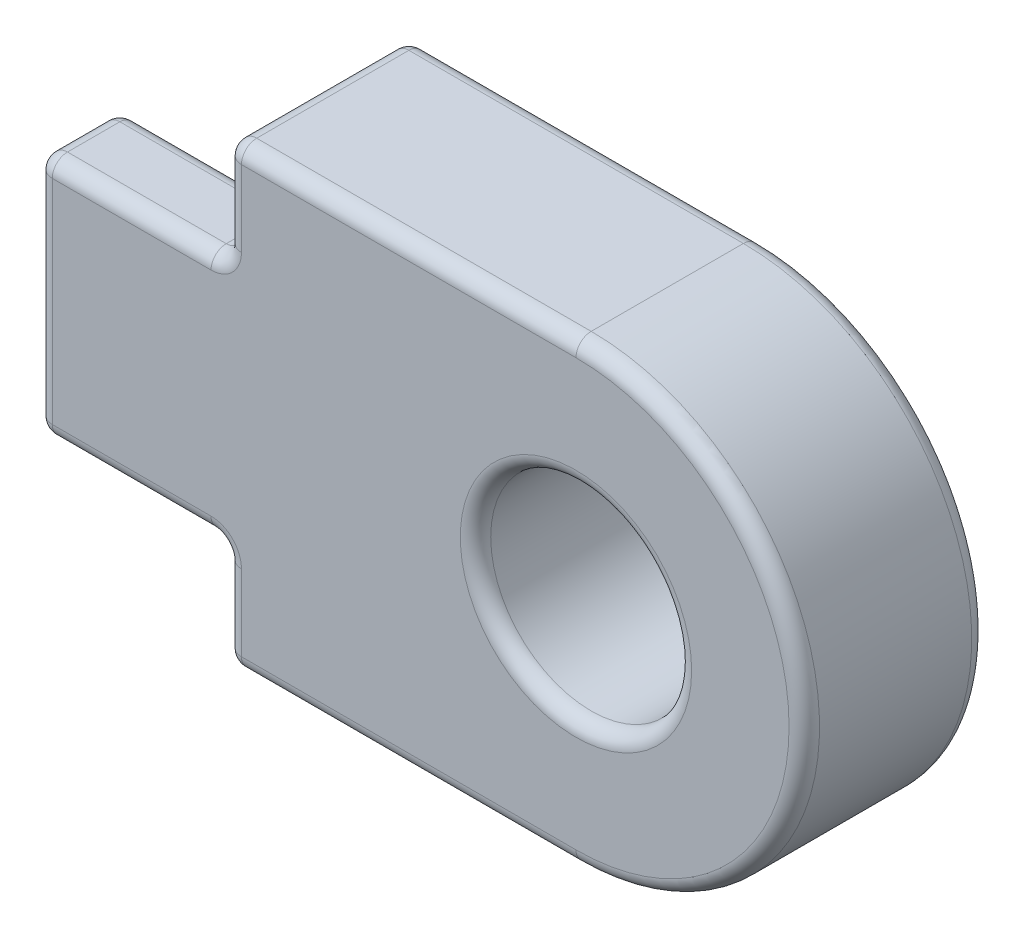
SolidWorks part; units mm, degrees
ref_plane "Front Plane" through (0, 0, 0) normal (1, 0, 0) x (0, 1, 0)
ref_plane "Top Plane" through (0, 0, 0) normal (0, 0, 1) x (0, 1, 0)
ref_plane "Right Plane" through (0, 0, 0) normal (0, 1, 0) x (-1, 0, 0)
sketch "Sketch1" plane through (0, 0, 0) normal (0, 0, 1) x (0, 1, 0)
  line L0 (-3.75, 0) -> (-3.75, 5.7439)
  line L1 (-3.75, 5.7439) -> (3.75, 5.7439)
  line L2 (3.75, 5.7439) -> (3.75, 0)
  circle A0 centre (0, 0) radius 1.65
  arc A1 (-3.75, 0) -> (3.75, 0) centre (0, 0) ccw
  dimension "D1" = 3.3
  dimension "D2" = 7.5
extrude "Boss-Extrude1" add sketch "Sketch1" along normal blind 3
sketch "Sketch2" plane through (0, 0, 0) normal (0, 1, 0) x (-1, 0, 0)
  line L0 (5.7439, 3) -> (8.8511, 3)
  line L1 (8.8511, 3) -> (8.8511, 1.64)
  line L2 (8.9, 1.64) -> (8.1, 1.64) construction
  line L3 (8.8511, 1.64) -> (5.7439, 1.64)
  line L4 (5.7439, 3) -> (5.7439, 0) construction
  line L5 (5.7439, 1.64) -> (5.7439, 3)
extrude "Boss-Extrude2" add sketch "Sketch2" against normal blind 2 and the other way blind 2
fillet "Fillet1" radius 0.25 24 edges at (-5.7439, 3.75, 1.5) (-5.7439, -3.75, 1.5) (-2.872, -3.75, 0) (-2.872, -3.75, 3) (-5.7439, 2.875, 3) (-5.7439, -2.875, 3) (-2.872, 3.75, 0) (-2.872, 3.75, 3) (3.75, 0, 0) (3.75, 0, 3) (-5.7439, 0, 0) (1.65, 0, 3) (1.65, 0, 0) (-5.7439, 0, 1.64) (-8.8511, 0, 1.64) (-8.8511, 0, 3) (-7.2975, 2, 3) (-8.8511, 2, 2.32) (-7.2975, 2, 1.64) (-5.7439, 2, 2.32) (-7.2975, -2, 3) (-8.8511, -2, 2.32) (-7.2975, -2, 1.64) (-5.7439, -2, 2.32)
